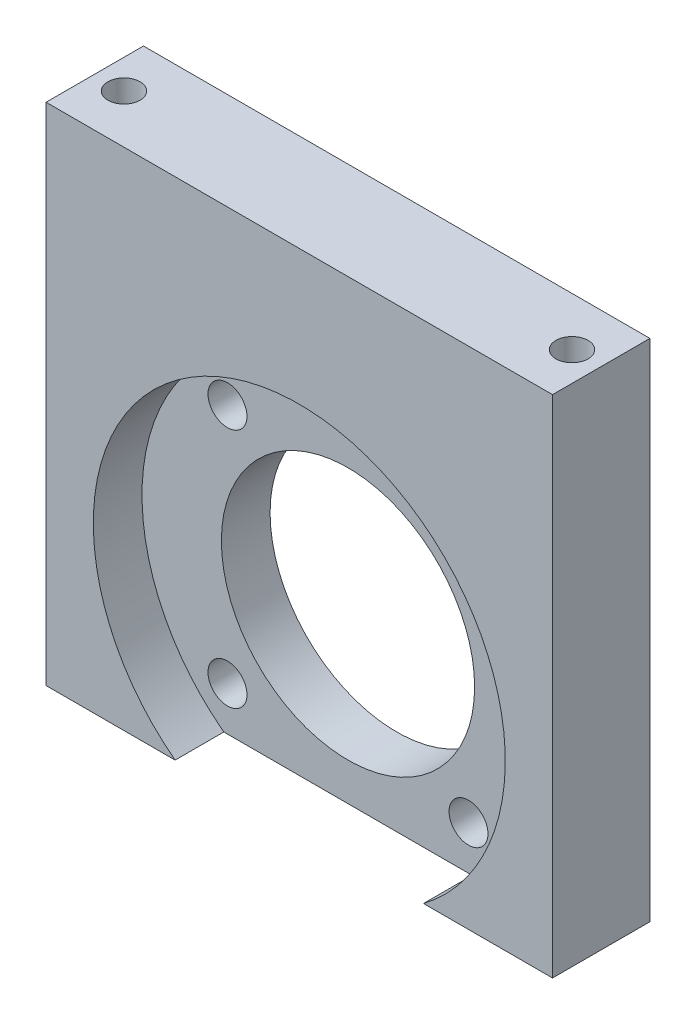
SolidWorks part; units mm, degrees
ref_plane "前视基准面" through (0, 0, 0) normal (0, 0, 1) x (1, 0, 0)
ref_plane "上视基准面" through (0, 0, 0) normal (0, 1, 0) x (1, 0, 0)
ref_plane "右视基准面" through (0, 0, 0) normal (1, 0, 0) x (0, 0, -1)
sketch "草图1" plane through (0, 0, 0) normal (0, 1, 0) x (1, 0, 0)
  line L0 (0, 0) -> (52, 0)
  line L1 (52, 0) -> (52, 20)
  line L2 (52, 20) -> (0, 20)
  line L3 (0, 20) -> (0, 0)
  dimension "D1" = 52
  dimension "D2" = 20
extrude "凸台-拉伸4" add sketch "草图1" along normal blind 50
sketch "草图11" plane through (0, 0, 0) normal (0, 0, 1) x (1, 0, 0)
  line L0 (26, 50) -> (26, 0) construction
  line L1 (0, 50) -> (52, 50) construction
  line L2 (0, 0) -> (52, 0) construction
  line L3 (0, 25) -> (52, 25) construction
  line L4 (0, 50) -> (0, 0) construction
  line L5 (52, 50) -> (52, 0) construction
  circle A0 centre (26, 25) radius 21.15
  dimension "D1" = 42.3
extrude "切除-拉伸7" cut sketch "草图11" against normal blind 13
sketch "草图13" plane through (0, 0, -13) normal (0, 0, 1) x (1, 0, 0)
  line L0 (26, 25) -> (26, 50) construction
  line L1 (0, 50) -> (52, 50) construction
  line L2 (26, 25) -> (0, 25) construction
  line L3 (0, 50) -> (0, 0) construction
  line L4 (0, 50) -> (26, 25) construction
  circle A0 centre (26, 25) radius 17.5 construction
  circle A1 centre (13, 37.5) radius 2
  circle A2 centre (38, 37) radius 2
  circle A3 centre (37.5, 12) radius 2
  circle A4 centre (12.5, 12.5) radius 2
  point P22 (25.25, 24.75)
  dimension "D1" = 35
  dimension "D2" = 4
  dimension "D3" = 4
sketch "草图14" plane through (0, 0, -13) normal (0, 0, 1) x (1, 0, 0)
  circle A0 centre (26, 25) radius 13
  dimension "D1" = 26
extrude "切除-拉伸9" cut sketch "草图14" against normal blind 15
sketch "草图18" plane through (0, 0, -20) normal (0, 0, -1) x (-1, 0, 0)
  line L0 (-26, 25) -> (-26, 50) construction
  line L1 (-52, 50) -> (0, 50) construction
  line L2 (-26, 25) -> (-52, 25) construction
  line L3 (-52, 50) -> (-52, 0) construction
  line L4 (-26, 25) -> (-45.288, 44.288) construction
  line L5 (-26, 25) -> (-25.9388, 25) construction
  circle A0 centre (-26, 25) radius 17.5 construction
  circle A6 centre (-38.3744, 37.3744) radius 1.65
  circle A7 centre (-13.6256, 37.3744) radius 1.65
  circle A8 centre (-13.6256, 12.6256) radius 1.65
  circle A9 centre (-38.3744, 12.6256) radius 1.65
  point P22 (-25.7426, 25.4976)
  dimension "D1" = 35
  dimension "D2" = 45
  dimension "D3" = 3.3
sketch "草图54" plane through (0, 0, -20) normal (0, 0, -1) x (-1, 0, 0)
  line L0 (-26, 25) -> (-52, 25) construction
  line L1 (-52, 50) -> (-52, 0) construction
  line L2 (-26, 25) -> (-26, 50) construction
  line L3 (-52, 50) -> (0, 50) construction
  line L4 (-26, 25) -> (-42.8928, 41.8928) construction
  line L5 (-26, 25) -> (-25.9173, 25) construction
  circle A0 centre (-26, 25) radius 17.5 construction
  circle A1 centre (-38.3744, 37.3744) radius 2
  circle A2 centre (-13.6256, 37.3744) radius 2
  circle A3 centre (-13.6256, 12.6256) radius 2
  circle A4 centre (-38.3744, 12.6256) radius 2
  dimension "D1" = 35
  dimension "D2" = 4
  dimension "D3" = 135
sketch "草图56" plane through (0, 0, -20) normal (0, 0, -1) x (-1, 0, 0)
  line L0 (-38.3744, 12.6256) -> (-38.3744, 8.1256) construction
  line L1 (-38.3744, 8.1256) -> (-52, 8.1256)
  line L2 (-52, 50) -> (-52, 0) construction
  line L3 (-52, 8.1256) -> (-52, 0)
  line L4 (-52, 0) -> (0, 0)
  line L5 (0, 0) -> (0, 8.1256)
  line L6 (0, 50) -> (0, 0) construction
  line L7 (0, 8.1256) -> (-38.3744, 8.1256)
  dimension "D1" = 4.5
extrude "切除-拉伸13" cut sketch "草图56" against normal blind 35
sketch "草图57" plane through (0, 50, 0) normal (0, 1, 0) x (1, 0, 0)
  line L0 (0, 0) -> (4, 0) construction
  line L1 (0, 0) -> (52, 0) construction
  line L2 (4, 0) -> (4, 5) construction
  line L3 (26, 20) -> (26, 0) construction
  line L4 (43.5, 20) -> (8.5, 20) construction
  line L5 (0, 10) -> (52, 10) construction
  line L6 (0, 20) -> (0, 0) construction
  line L7 (52, 0) -> (52, 20) construction
  circle A0 centre (4, 5) radius 2
  circle A1 centre (4, 15) radius 2
  circle A2 centre (48, 5) radius 2
  circle A3 centre (48, 15) radius 2
  dimension "D3" = 4
  dimension "D1" = 4
  dimension "D2" = 5
sketch "草图60" plane through (0, 8.1256, 0) normal (0, -1, 0) x (1, 0, 0)
  line L0 (0, 0) -> (3, 0) construction
  line L1 (3, 0) -> (3, -5) construction
  line L2 (26, 0) -> (26, -20) construction
  line L3 (0, -10) -> (52, -10) construction
  circle A0 centre (3, -5) radius 1.65
  circle A1 centre (3, -15) radius 1.65
  circle A2 centre (49, -15) radius 1.65
  circle A3 centre (49, -5) radius 1.65
  dimension "D3" = 3.3
  dimension "D1" = 3
  dimension "D2" = 5
hole_wizard "大小mm 暗销孔6" positions "3D草图24" profile "草图61" hole size "Ø1.0" standard "GB"
sketch3d "3D草图24"
  point P0 (3, 8.1256, -5)
  point P3 (3, 8.1256, -15)
  point P6 (49, 8.1256, -5)
  point P9 (49, 8.1256, -15)
  point P12 (0, 0, 0)
sketch "草图61" plane through (3, 8.1256, -5) normal (1, 0, 0) x (0, 0, -1)
  line L0 (0, 0) -> (0, 15.9914)
  line L1 (0, 15.9914) -> (1.65, 15)
  line L2 (1.65, 15) -> (1.65, 0)
  line L5 (1.65, 0) -> (0, 0)
  line L10 (0, 15.9914) -> (-1.65, 15) construction
  line L11 (0, -6.35) -> (0, 107.95) construction
  dimension "孔直径" = 3.3
  dimension "孔深度" = 15
  dimension "导头角度" = 118
sketch "草图62" plane through (0, 50, 0) normal (0, 1, 0) x (1, 0, 0)
  line L0 (0, 10) -> (52, 10)
  line L1 (0, 20) -> (0, 0) construction
  line L2 (52, 0) -> (52, 20) construction
  line L3 (52, 10) -> (52, 0)
  line L4 (52, 0) -> (0, 0)
  line L5 (0, 0) -> (0, 10)
extrude "切除-拉伸14" cut sketch "草图62" against normal blind 97
sketch "草图63" plane through (0, 0, -13) normal (0, 0, 1) x (1, 0, 0)
  circle A0 centre (26, 25) radius 21.15
extrude "切除-拉伸15" cut sketch "草图63" against normal blind 2
sketch "草图65" plane through (0, 0, -20) normal (0, 0, -1) x (-1, 0, 0)
  line L0 (-26, 25) -> (-26, 50) construction
  line L1 (-52, 50) -> (0, 50) construction
extrude "切除-拉伸18" cut sketch "草图54" against normal blind 10
sketch "草图68" plane through (0, 50, 0) normal (0, 1, 0) x (1, 0, 0)
  line L1 (0, 20) -> (52, 20)
  line L2 (0, 20) -> (0, 10)
  line L3 (0, 10) -> (52, 10)
  line L4 (52, 20) -> (52, 10)
sketch "草图76" plane through (0, 50, 0) normal (0, 1, 0) x (1, 0, 0)
  line L1 (52, 10) -> (0, 10)
  line L2 (52, 10) -> (52, 20)
  line L3 (52, 20) -> (0, 20)
  line L4 (0, 10) -> (0, 20)
extrude "凸台-拉伸7" add sketch "草图76" along normal blind 10
sketch "草图78" plane through (0, 60, 0) normal (0, 1, 0) x (1, 0, 0)
  point P0 (3, 15)
  point P3 (49, 15)
hole_wizard "Ø1.0mm 暗销孔1" positions "草图78" profile "草图79" hole size "Ø1.0" standard "GB"
sketch "草图79" plane through (3, 60, -15) normal (1, 0, 0) x (0, 0, 1)
  line L0 (0, 0) -> (0, 15.9914)
  line L1 (0, 15.9914) -> (1.65, 15)
  line L2 (1.65, 15) -> (1.65, 0)
  line L5 (1.65, 0) -> (0, 0)
  line L10 (0, 15.9914) -> (-1.65, 15) construction
  line L11 (0, -6.35) -> (0, 107.95) construction
  dimension "孔直径" = 3.3
  dimension "孔深度" = 15
  dimension "导头角度" = 118
